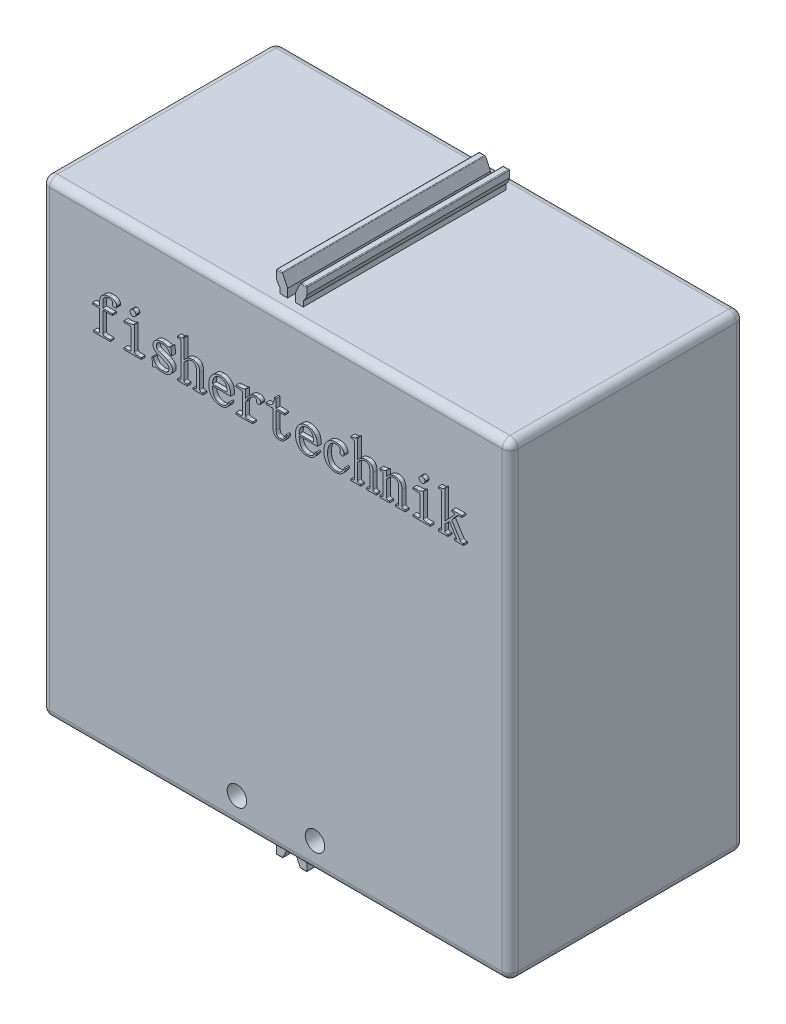
SolidWorks part; units mm, degrees
ref_plane "前视基准面" through (0, 0, 0) normal (0, 0, 1) x (1, 0, 0)
ref_plane "上视基准面" through (0, 0, 0) normal (0, 1, 0) x (1, 0, 0)
ref_plane "右视基准面" through (0, 0, 0) normal (1, 0, 0) x (0, 0, -1)
sketch "草图1" plane through (0, 0, 0) normal (0, 0, 1) x (1, 0, 0)
  line L1 (-30, 0) -> (30, 0)
  line L2 (-30, 0) -> (-30, 60)
  line L3 (-30, 60) -> (30, 60)
  line L4 (30, 0) -> (30, 60)
extrude "凸台-拉伸1" add sketch "草图1" against normal blind 30
sketch "草图2" plane through (0, 0, 0) normal (0, 0, 1) x (1, 0, 0)
  line L0 (30, 60) -> (-30, 60) construction
  line L1 (-1.5, 60) -> (-0.5, 60)
  line L2 (-1.5, 60) -> (-1.5, 60.6771)
  line L3 (0.5, 61.0723) -> (1.1658, 62.5)
  line L4 (1.5, 60) -> (1.5, 60.6771)
  line L5 (-1.95, 62.5) -> (-1.1658, 62.5)
  line L6 (-1.95, 62.5) -> (-1.95, 61.5556)
  line L7 (1.95, 62.5) -> (1.95, 61.5556)
  line L8 (-0.5, 61.0723) -> (-1.1658, 62.5)
  line L9 (1.1658, 62.5) -> (1.95, 62.5)
  line L10 (-32, 30) -> (32, 30) construction
  line L11 (-0.5, 60) -> (-0.5, 61.0723)
  line L12 (0.5, 0) -> (1.5, 0)
  line L13 (0.5, 60) -> (0.5, 61.0723)
  line L14 (0.5, 0) -> (0.5, -1.0723)
  line L15 (0.5, 60) -> (1.5, 60)
  line L16 (-0.5, 0) -> (-0.5, -1.0723)
  line L17 (1.1658, -2.5) -> (1.95, -2.5)
  line L18 (-0.5, -1.0723) -> (-1.1658, -2.5)
  line L19 (1.95, -2.5) -> (1.95, -1.5556)
  line L20 (-1.95, -2.5) -> (-1.95, -1.5556)
  line L21 (-1.95, -2.5) -> (-1.1658, -2.5)
  line L22 (1.5, 0) -> (1.5, -0.6771)
  line L23 (0.5, -1.0723) -> (1.1658, -2.5)
  line L24 (-1.5, 0) -> (-1.5, -0.6771)
  line L25 (-1.5, 0) -> (-0.5, 0)
  arc A0 (1.5, -0.6771) -> (1.95, -1.5556) centre (0, -2) cw
  arc A1 (-1.95, 61.5556) -> (-1.5, 60.6771) centre (0, 62) ccw
  arc A2 (1.5, 60.6771) -> (1.95, 61.5556) centre (0, 62) ccw
  arc A3 (-1.95, -1.5556) -> (-1.5, -0.6771) centre (0, -2) cw
extrude "凸台-拉伸2" add sketch "草图2" against normal blind 26 from offset 2 offset against normal yes
sketch "草图3" plane through (0, 0, 0) normal (0, 0, 1) x (1, 0, 0)
  circle A0 centre (-5, 3.5) radius 1.25
  circle A1 centre (5, 3.5) radius 1.25
extrude "切除-拉伸1" cut sketch "草图3" against normal blind 5
fillet "圆角1" radius 1 12 edges at (-30, 0, -15) (-30, 30, -30) (-30, 60, -15) (-30, 30, 0) (30, 60, -15) (30, 30, -30) (30, 0, -15) (30, 30, 0) (0, 0, 0) (0, 0, -30) (0, 60, -30) (0, 60, 0)
fillet "圆角2" radius 0.1 16 edges at (1.95, -2.5, -15) (1.5579, -2.5, -28) (1.1658, -2.5, -15) (1.5579, -2.5, -2) (-1.1658, -2.5, -15) (-1.5579, -2.5, -28) (-1.95, -2.5, -15) (-1.5579, -2.5, -2) (1.1658, 62.5, -15) (1.5579, 62.5, -28) (1.95, 62.5, -15) (1.5579, 62.5, -2) (-1.95, 62.5, -15) (-1.5579, 62.5, -28) (-1.1658, 62.5, -15) (-1.5579, 62.5, -2)
sketch "草图5" plane through (0, 0, 0) normal (0, 0, 1) x (1, 0, 0)
  text T0 "fishertechnik" font "宋体" height in points 14
extrude "凸台-拉伸3" add sketch "草图5" along normal blind 0.5
